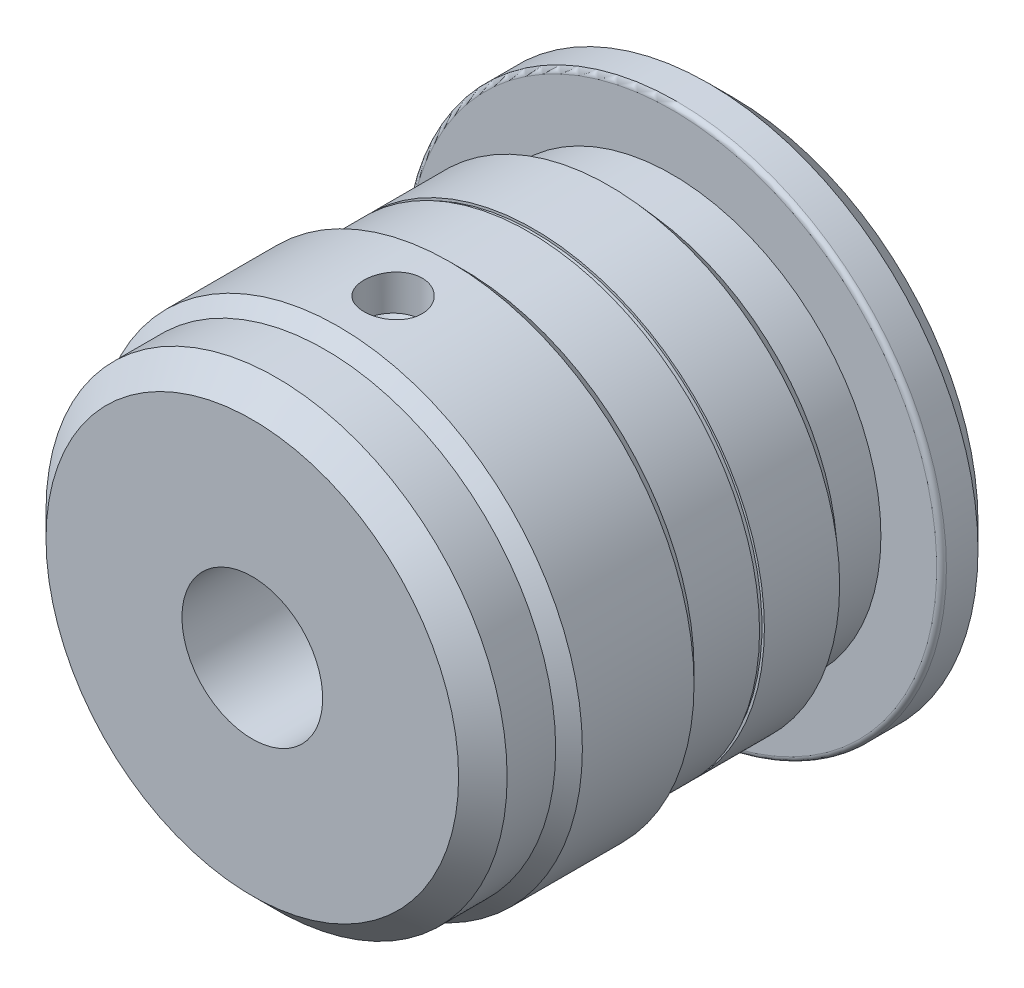
SolidWorks part; units mm, degrees
ref_plane "정면" through (0, 0, 0) normal (0, 0, 1) x (1, 0, 0)
ref_plane "윗면" through (0, 0, 0) normal (0, 1, 0) x (1, 0, 0)
ref_plane "우측면" through (0, 0, 0) normal (1, 0, 0) x (0, 0, -1)
sketch "스케치3" plane through (0, 0, 0) normal (0, 1, 0) x (1, 0, 0)
  line L0 (0, 0) -> (0, -21.8) construction
  line L1 (11.1, 0) -> (11.1, -2.5)
  line L2 (11.1, -2.5) -> (8.6, -2.5)
  line L3 (11.1, 0) -> (6.1, 0)
  line L4 (8.6, -2.5) -> (8.6, -4.3)
  line L5 (8.6, -4.3) -> (9.5, -5.1)
  line L6 (11.1, 0) -> (11.1, -8.2) construction
  line L7 (9.5, -8.2) -> (9.4, -8.2)
  line L8 (10.05, -16.25) -> (9.5, -16.8)
  line L9 (9.4, -8.2) -> (9.4, -8.4)
  line L10 (9.5, -5.1) -> (9.5, -8.2)
  line L11 (9.4, -8.4) -> (9.5, -8.4)
  line L12 (9.5, -19.8) -> (2.9, -19.8)
  line L13 (2.9, -19.8) -> (2.9, -11.8)
  line L14 (2.9, -11.8) -> (4.4, -11.8)
  line L15 (4.4, -11.8) -> (4.4, -10)
  line L16 (4.4, -10) -> (3.4, -10)
  line L17 (3.4, -10) -> (3.4, -8.5)
  line L18 (3.4, -8.5) -> (6.1, -7.7765)
  line L19 (6.1, -7.7765) -> (6.1, 0)
  line L20 (0, 0) -> (6.1, 0) construction
  line L21 (9.5, -11.1) -> (10.05, -11.65)
  line L22 (9.5, -8.4) -> (9.5, -11.1)
  line L23 (9.5, -8.2) -> (11.1, -8.2) construction
  line L34 (10.05, -11.65) -> (10.05, -16.25)
  line L37 (9.5, -16.8) -> (9.5, -19.8)
  dimension "D2" = 19
  dimension "D3" = 2.5
  dimension "D4" = 0.8
  dimension "D5" = 1.8
  dimension "D6" = 6
  dimension "D7" = 12.2
  dimension "D8" = 5.8
  dimension "D9" = 8.2
  dimension "D10" = 17.2
  dimension "D11" = 8
  dimension "D12" = 3
  dimension "D13" = 10
  dimension "D14" = 8.8
  dimension "D15" = 6.8
  dimension "D16" = 105
  dimension "D17" = 1.8
  dimension "D18" = 1.5
  dimension "D19" = 22.2
  dimension "D20" = 135
  dimension "D21" = 135
  dimension "D23" = 0.1
  dimension "D22" = 20.1
  dimension "D24" = 0.2
revolve "회전2" add sketch "스케치3" angle 360 about L0
chamfer "모따기1" distance 1 angle 45 2 edges at (-6.1, 0, 0) (-9.5, 0, 19.8)
chamfer "모따기2" distance 1 angle 45 1 edges at (-11.1, 0, 0)
fillet "필렛1" radius 0.2 1 edges at (-11.1, 0, 2.5)
ref_plane "평면1" through (0, 10.05, 0) normal (0, 1, 0) x (1, 0, 0)
sketch "스케치4" plane through (0, 10.05, 0) normal (0, 1, 0) x (1, 0, 0)
  line L0 (0, 0) -> (0, -14) construction
  line L1 (0, -14) -> (6, -14) construction
  circle A0 centre (6, -14) radius 1
  dimension "D1" = 2
  dimension "D2" = 6
  dimension "D3" = 14
extrude "컷-돌출1" [suppressed] cut sketch "스케치4" against normal blind 20
mirror "대칭 복사1" [suppressed] about plane through (0, 0, 0) normal (1, 0, 0)
sketch "스케치5" plane through (0, 10.05, 0) normal (0, 1, 0) x (1, 0, 0)
  line L0 (0, 0) -> (0, -14) construction
  line L1 (10.1, 0) -> (-10.1, 0) construction
  circle A0 centre (0, -14) radius 1.2
  dimension "D1" = 2.4
  dimension "D2" = 14
extrude "컷-돌출2" cut sketch "스케치5" against normal blind 2
chamfer "모따기3" distance 0.5 angle 45 1 edges at (0, 8.05, 15.2)
pattern_circular "원형 패턴1" count 2 over 360 about axis through (0, 0, 0) along (0, 0, -1) of "컷-돌출2", "모따기3"
